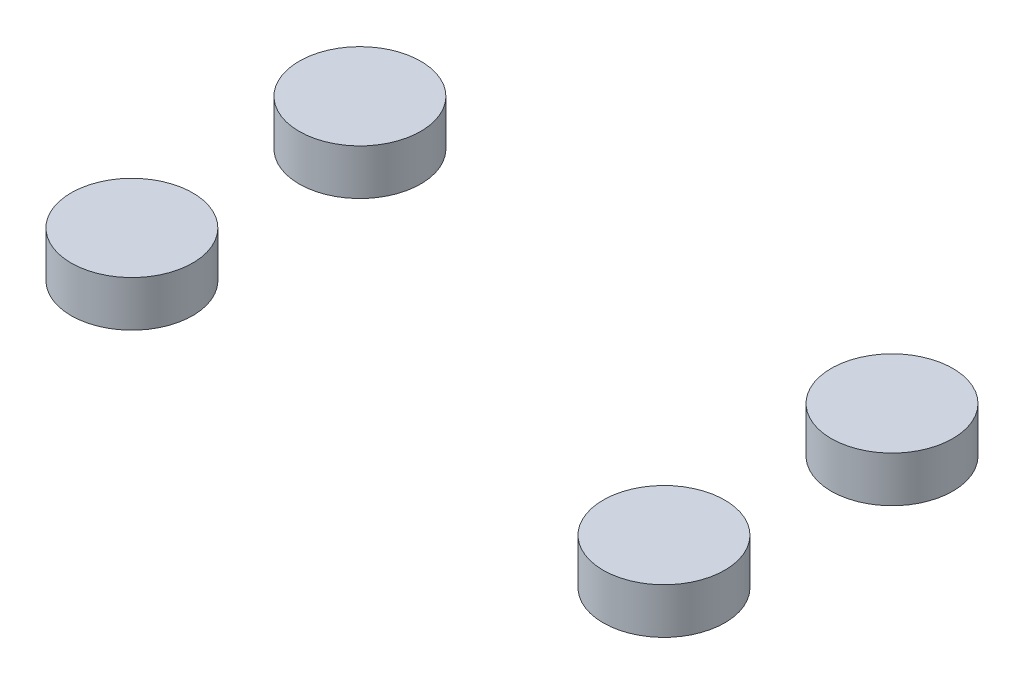
SolidWorks part; units mm, degrees
ref_plane "Front Plane" through (0, 0, 0) normal (0, 0, 1) x (1, 0, 0)
ref_plane "Top Plane" through (0, 0, 0) normal (0, 1, 0) x (1, 0, 0)
ref_plane "Right Plane" through (0, 0, 0) normal (1, 0, 0) x (0, 0, -1)
sketch "Sketch1" plane through (0, 0, 0) normal (0, 1, 0) x (1, 0, 0)
  circle A0 centre (-700, 1940) radius 160
extrude "Boss-Extrude1" add sketch "Sketch1" along normal blind 120 from offset 140
sketch "Sketch2" plane through (0, 0, 0) normal (0, 1, 0) x (1, 0, 0)
  circle A0 centre (-700, 1340) radius 160
extrude "Boss-Extrude2" add sketch "Sketch2" along normal blind 120 from offset 140
sketch "Sketch3" plane through (0, 0, 0) normal (0, 1, 0) x (1, 0, 0)
  circle A0 centre (700, 1940) radius 160
extrude "Boss-Extrude3" add sketch "Sketch3" along normal blind 120 from offset 140
sketch "Sketch4" plane through (0, 0, 0) normal (0, 1, 0) x (1, 0, 0)
  circle A0 centre (700, 1340) radius 160
extrude "Boss-Extrude4" add sketch "Sketch4" along normal blind 120 from offset 140
